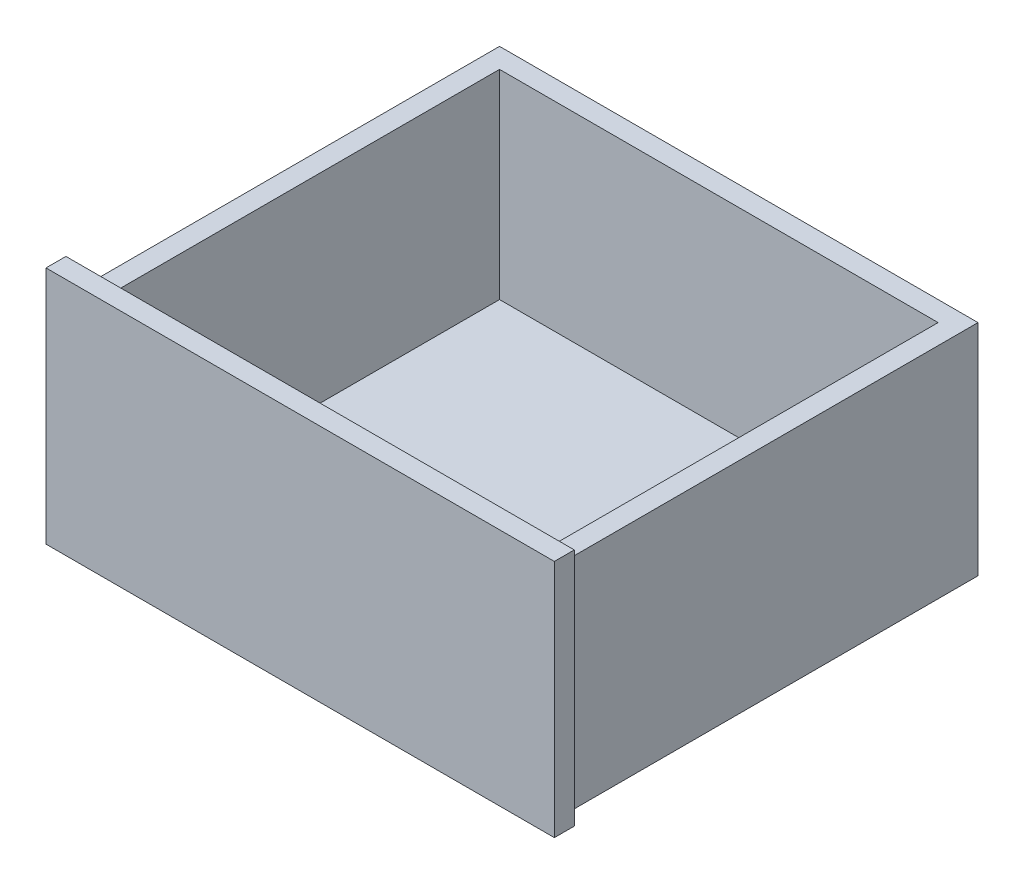
SolidWorks part; units mm, degrees
ref_plane "Front Plane" through (0, 0, 0) normal (0, 0, 1) x (1, 0, 0)
ref_plane "Top Plane" through (0, 0, 0) normal (0, 1, 0) x (1, 0, 0)
ref_plane "Right Plane" through (0, 0, 0) normal (1, 0, 0) x (0, 0, -1)
sketch "Sketch1" plane through (0, 0, 0) normal (0, 0, 1) x (1, 0, 0)
  line L1 (-32.385, -15.24) -> (32.385, -15.24)
  line L2 (-32.385, -15.24) -> (-32.385, 15.24)
  line L3 (-32.385, 15.24) -> (32.385, 15.24)
  line L4 (32.385, -15.24) -> (32.385, 15.24)
  line L5 (-32.385, -15.24) -> (32.385, 15.24) construction
  line L6 (-32.385, 15.24) -> (32.385, -15.24) construction
  point P0 (0, 0)
  dimension "D1" = 30.48
  dimension "D2" = 64.77
extrude "Boss-Extrude1" add sketch "Sketch1" along normal blind 2.54
sketch "Sketch2" plane through (0, -15.24, 0) normal (0, -1, 0) x (1, 0, 0)
  line L0 (-32.385, 0) -> (32.385, 0) construction
  line L1 (-30.48, 0) -> (30.48, 0)
  line L2 (-30.48, 0) -> (-30.48, -53.34)
  line L3 (-30.48, -53.34) -> (30.48, -53.34)
  line L4 (30.48, 0) -> (30.48, -53.34)
  line L5 (0, 0) -> (0, -53.34) construction
  dimension "D1" = 53.34
  dimension "D2" = 60.96
extrude "Boss-Extrude2" add sketch "Sketch2" against normal blind 2.54 separate body
sketch "Sketch3" plane through (0, -12.7, 0) normal (0, -1, 0) x (-1, 0, 0)
  line L0 (-32.385, 0) -> (32.385, 0) construction
  line L1 (27.94, 0) -> (-27.94, 0)
  line L2 (27.94, 0) -> (27.94, 50.8)
  line L3 (27.94, 50.8) -> (-27.94, 50.8)
  line L4 (-27.94, 0) -> (-27.94, 50.8)
  line L5 (0, 50.8) -> (0, 0) construction
  line L7 (30.48, 53.34) -> (-30.48, 53.34) construction
  line L9 (30.48, 53.34) -> (-30.48, 53.34)
  line L10 (30.48, 53.34) -> (30.48, 0)
  line L11 (30.48, 0) -> (-30.48, 0)
  line L12 (-30.48, 53.34) -> (-30.48, 0)
  line M21 (30.48, 53.34) -> (30.48, 0)
  line M22 (30.48, 0) -> (-30.48, 0)
  line M23 (-30.48, 0) -> (-30.48, 53.34)
  line M24 (-30.48, 53.34) -> (30.48, 53.34)
  dimension "D1" = 2.54
  dimension "D2" = 2.54
extrude "Boss-Extrude4" add sketch "Sketch3" against normal offset from surface (25.4 mm away) 2.54 contours L4 L2 L3 M22 M23 M24 M21 up to face at (0, 15.24, 1.27)
